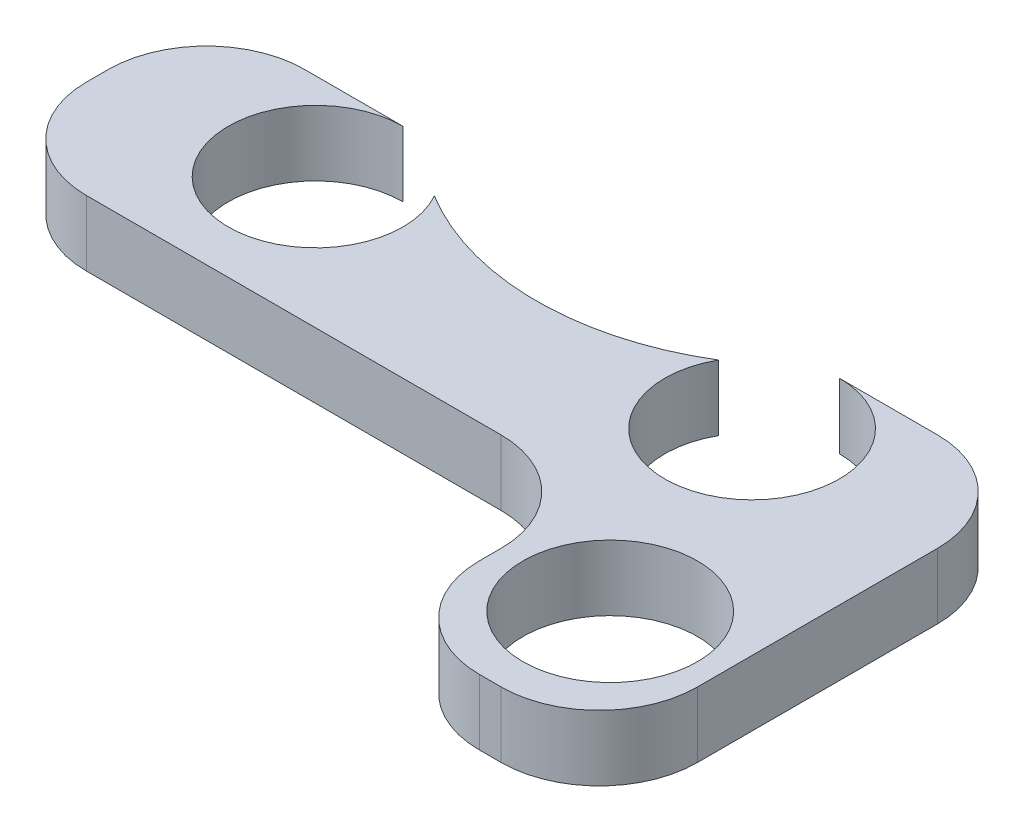
SolidWorks part; units mm, degrees
material "ONYX"
ref_plane "Front Plane" through (0, 0, 0) normal (0, 0, 1) x (1, 0, 0)
ref_plane "Top Plane" through (0, 0, 0) normal (0, 1, 0) x (1, 0, 0)
ref_plane "Right Plane" through (0, 0, 0) normal (1, 0, 0) x (0, 0, -1)
sketch "Sketch1" plane through (0, 0, 0) normal (0, 1, 0) x (1, 0, 0)
  line L5 (0, 25.2428) -> (0, -18.6244) construction
  line L9 (-10, -8.6244) -> (-14.5, -8.6244)
  line L11 (-19, -13.1244) -> (-19, -14.1244)
  line L12 (14.5, -8.6244) -> (10, -8.6244)
  line L13 (-50, -5.1244) -> (83.0072, -5.1244) construction
  line L14 (-14.5, -18.6244) -> (4.5, -18.6244)
  line L16 (9, -23.1244) -> (9, -24.1244)
  line L17 (13.5, -28.6244) -> (14.5, -28.6244)
  line L18 (19, -24.1244) -> (19, -13.1244)
  line L19 (9, -23.1244) -> (19, -23.1244) construction
  line L20 (14, -28.6244) -> (14, -8.6244) construction
  circle A5 centre (0, 0.5) radius 12.5 construction
  arc A6 (6.5091, -10.6715) -> (10, -8.6244) centre (10, -12.6244) ccw
  arc A7 (-6.5091, -10.6715) -> (-10, -8.6244) centre (-10, -12.6244) cw
  circle A8 centre (0, 11.9164) radius 22.5 construction
  arc A9 (-6.5091, -10.6715) -> (6.5091, -10.6715) centre (0, 0) ccw
  circle A10 centre (-10, -12.6244) radius 4 construction
  circle A11 centre (10, -12.6244) radius 4 construction
  circle A12 centre (14, -23.1244) radius 4
  arc A13 (14.5, -8.6244) -> (19, -13.1244) centre (14.5, -13.1244) cw
  arc A14 (-14.5, -8.6244) -> (-19, -13.1244) centre (-14.5, -13.1244) ccw
  arc A15 (14.5, -28.6244) -> (19, -24.1244) centre (14.5, -24.1244) ccw
  arc A16 (9, -24.1244) -> (13.5, -28.6244) centre (13.5, -24.1244) ccw
  arc A17 (9, -23.1244) -> (4.5, -18.6244) centre (4.5, -23.1244) ccw
  arc A18 (-19, -14.1244) -> (-14.5, -18.6244) centre (-14.5, -14.1244) ccw
  point P33 (19, -8.6244)
  point P36 (-19, -8.6244)
  point P39 (19, -28.6244)
  point P42 (9, -28.6244)
  point P45 (9, -18.6244)
  point P48 (-19, -18.6244)
  dimension "D1" = 25
  dimension "D2" = 8
  dimension "D4" = 12.5
  dimension "D11" = 45
  dimension "D14" = 8
  dimension "D16" = 4.5
  dimension "D3" = 10
  dimension "D5" = 0.5
  dimension "D6" = 9
  dimension "D7" = 10
  dimension "D8" = 9
  dimension "D9" = 13.5
  dimension "D10" = 50
  dimension "D12" = 10
  dimension "D13" = 10
  dimension "D15" = 5.5
extrude "Boss-Extrude1" add sketch "Sketch1" along normal mid plane 3
sketch "Sketch2" plane through (0, 1.5, 0) normal (0, 1, 0) x (1, 0, 0)
  line L0 (14, -19.1244) -> (14, -23.1244) construction
  circle A0 centre (14, -23.1244) radius 4 construction
  circle A1 centre (14, -23.1244) radius 3.5 construction
  dimension "D1" = 7
